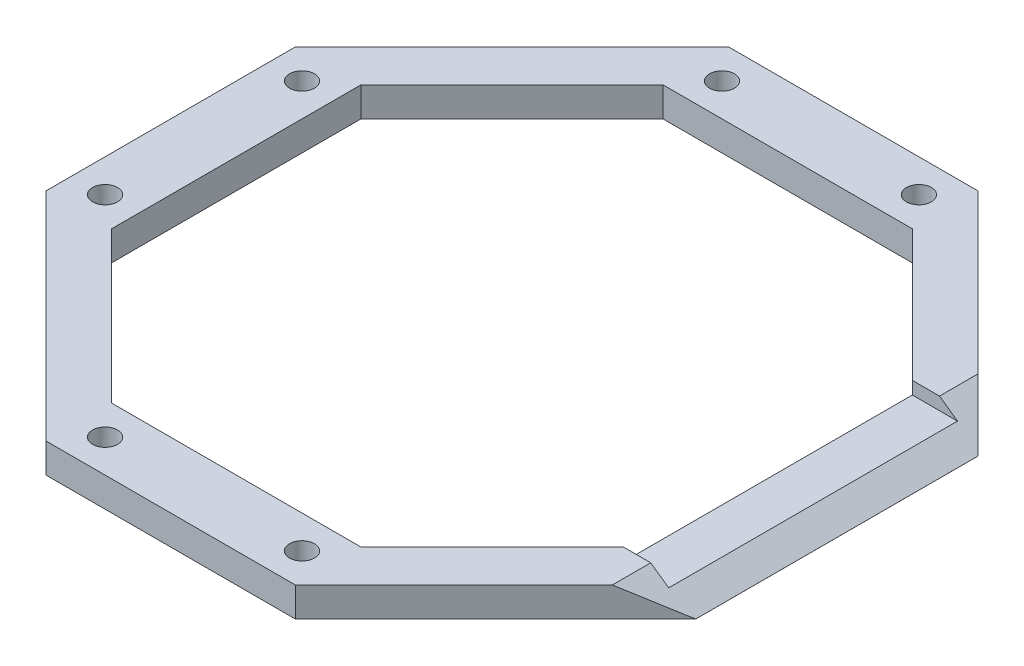
SolidWorks part; units mm, degrees
ref_plane "Front Plane" through (0, 0, 0) normal (0, 0, 1) x (1, 0, 0)
ref_plane "Top Plane" through (0, 0, 0) normal (0, 1, 0) x (1, 0, 0)
ref_plane "Right Plane" through (0, 0, 0) normal (1, 0, 0) x (0, 0, -1)
sketch "Sketch9" plane through (0, 0, 0) normal (0, 1, 0) x (1, 0, 0)
  line L0 (0.003, -52.003) -> (0.003, 51.997) construction
  line L9 (19.003, -51.997) -> (-18.997, -51.997)
  line L11 (19.003, 51.997) -> (-18.997, 51.997)
  line L12 (-51.997, -18.997) -> (-51.997, 18.997)
  line L13 (-52, 0) -> (52, 0) construction
  line L16 (-18.997, -51.997) -> (-51.997, -18.997)
  line L17 (-51.997, 18.997) -> (-18.997, 51.997)
  line L18 (-41.997, -18.997) -> (-41.997, 18.997)
  line L19 (-18.997, 41.997) -> (18.997, 41.997)
  line L21 (18.997, -41.997) -> (-18.997, -41.997)
  line L22 (-41.997, 18.997) -> (-18.997, 41.997)
  line L25 (-18.997, -41.997) -> (-41.997, -18.997)
  line L26 (18.997, -41.997) -> (38.994, -22)
  line L27 (18.997, 41.997) -> (38.994, 22)
  line L28 (41.997, 18.997) -> (41.997, -18.997) [skipped]
  line L29 (18.997, 41.997) -> (41.997, 18.997) [skipped]
  line L30 (41.997, -18.997) -> (18.997, -41.997) [skipped]
  line L31 (38.994, 22) -> (38.994, -22)
  line L32 (49.494, 21.5) -> (49.494, -21.5)
  line L33 (49.494, -21.5) -> (19.003, -51.997)
  line L34 (19.003, 51.997) -> (49.494, 21.5)
  point P0 (0, 0)
  point P5 (0, 0)
  point P8 (-18.997, 51.997)
  point P9 (19.003, 51.997)
  point P16 (51.997, 18.997)
  point P17 (51.997, -19.003)
  point P18 (18.997, -51.997)
  point P19 (-19.003, -51.997)
  point P20 (-51.997, -18.997)
  point P21 (-51.997, 19.003)
  point P22 (0, 0)
  point P32 (0, 0)
  point P33 (49.494, 0)
  point P36 (0, 0)
  point P37 (47.0008, -14.0008)
  point P38 (14.0008, -47.0008)
  point P39 (-14.0008, -47.0008)
  point P40 (-47.0008, -14.0008)
  point P46 (0, 0)
  point P48 (0, 0)
  dimension "D1" = 38
  dimension "D2" = 10
  dimension "D3" = 19
  dimension "D4" = 44
  dimension "D7" = 46.669
  dimension "D8" = 4
  dimension "D9" = 32.5269
  dimension "D5" = 4
  dimension "D6" = 28.28
  dimension "D10" = 28.28
  dimension "D11" = 10.5
  dimension "D12" = 43
extrude "Boss-Extrude3" add sketch "Sketch9" along normal blind 4.5
sketch "Sketch13" plane through (0, 0, 51.997) normal (0, 0, 1) x (1, 0, 0)
  line L0 (0, 0) -> (49.5, 0)
  line L1 (19.003, 0) -> (49.494, 0) construction
  line L2 (49.5, 0) -> (43.1412, 4.5)
  line L3 (19.003, 4.5) -> (49.494, 4.5) construction
  line L4 (43.1412, 4.5) -> (0.003, 4.5)
  line L5 (-18.997, 4.5) -> (19.003, 4.5) construction
  line L6 (0.003, 4.5) -> (0, 0)
  line L7 (43.1412, 4.5) -> (43.1412, 18.6604)
  line L8 (43.1412, 18.6604) -> (64.2767, 15.0512)
  line L9 (64.2767, 15.0512) -> (49.5, 0)
  dimension "D1" = 7.79
  dimension "D2" = 49.5
extrude "Cut-Extrude4" cut sketch "Sketch13" against normal blind 96.5 contours L9 L8 L7 L2
sketch "Sketch14" plane through (38.994, 0, 0) normal (-1, 0, 0) x (0, 0, 1)
  line L0 (-22, 2.5632) -> (22, 2.5632)
  line L1 (-22, 4.5) -> (-22, 0) construction
  line L2 (22, 4.5) -> (22, 0) construction
  line L3 (22, 2.5632) -> (24.8234, 4.5632)
  line L4 (24.8234, 4.5632) -> (-24.8234, 4.5632)
  line L5 (-24.8234, 4.5632) -> (-22, 2.5632)
  line L6 (-18.997, 4.5) -> (18.997, 4.5) construction
  line L7 (-18.997, 4.5) -> (18.997, 4.5)
  line M6 (22, 0) -> (22, 4.5)
  line M7 (22, 4.5) -> (-22, 4.5)
  line M8 (-22, 4.5) -> (-22, 0)
  dimension "D1" = 2
  dimension "D2" = 3.46
  dimension "D3" = 3.46
extrude "Cut-Extrude5" cut sketch "Sketch14" against normal blind 32.5 contours L0 M8 M6 M7
hole_wizard "Ø4.0mm Press Dowel Hole3" positions "Sketch19" profile "Sketch20" hole size "Ø4.0" standard "ISO"
sketch "Sketch19" plane through (0, 4.5, 0) normal (0, 1, 0) x (1, 0, 0)
  line L0 (0, 0) -> (-74.0809, 0) construction
  line L2 (0, 0) -> (0, 56.1133) construction
  line L3 (0, 0) -> (0, -48.8997) construction
  line L4 (-51.997, 18.997) -> (-51.997, -18.997) construction
  line L6 (19.003, 51.997) -> (-18.997, 51.997) construction
  point P9 (-15, 46.997)
  point P18 (-46.997, 15)
  point P27 (15, 46.997)
  point P28 (15, -46.997)
  point P29 (-15, -46.997)
  point P30 (-46.997, -15)
  dimension "D1" = 15
  dimension "D2" = 15
  dimension "D3" = 5
  dimension "D4" = 5
sketch "Sketch20" plane through (-46.997, 4.5, 15) normal (1, 0, 0) x (0, 0, 1)
  line L0 (0, 0) -> (0, 61.587)
  line L1 (0, 61.587) -> (1.9, 57)
  line L2 (1.9, 57) -> (1.9, 0)
  line L5 (1.9, 0) -> (0, 0)
  line L10 (0, 61.587) -> (-1.9, 57) construction
  line L11 (0, -6.35) -> (0, 107.95) construction
  dimension "Hole Dia." = 3.8
  dimension "Hole Depth" = 57
  dimension "Drill Angle" = 45
